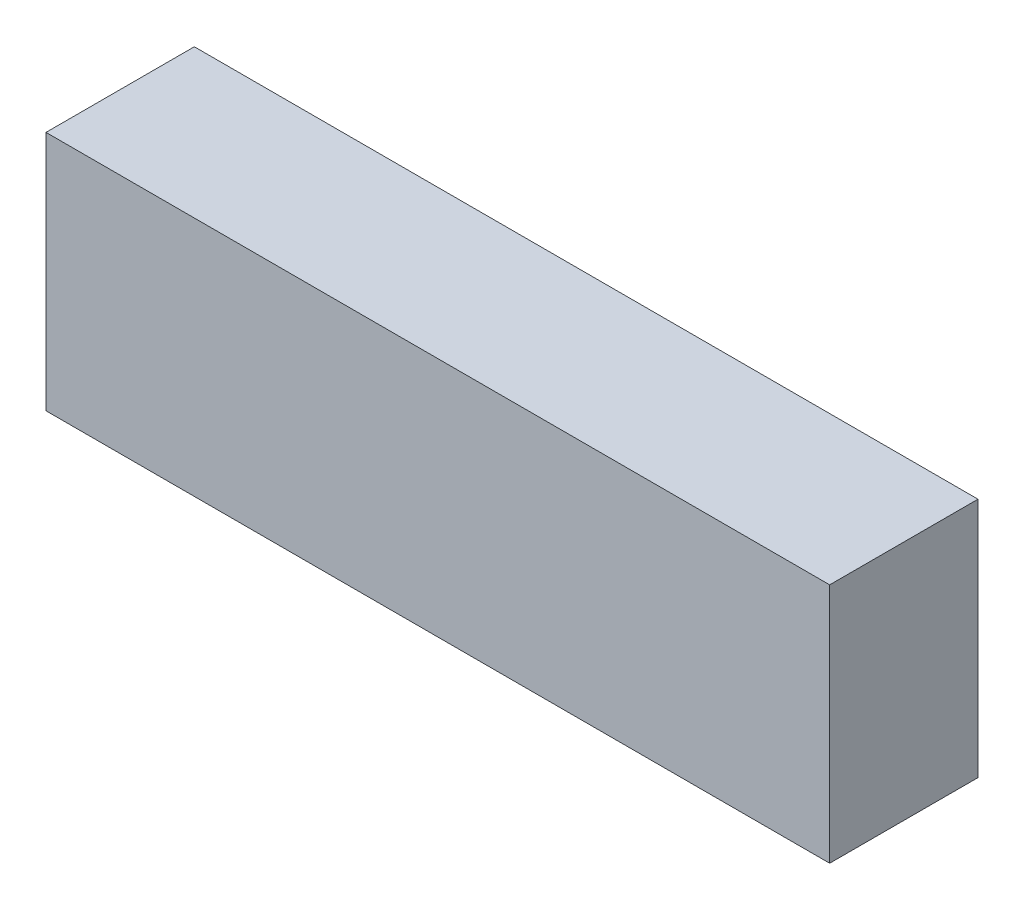
SolidWorks part; units mm, degrees
ref_plane "Front Plane" through (0, 0, 0) normal (0, 0, 1) x (1, 0, 0)
ref_plane "Top Plane" through (0, 0, 0) normal (0, 1, 0) x (1, 0, 0)
ref_plane "Right Plane" through (0, 0, 0) normal (1, 0, 0) x (0, 0, -1)
sketch "Sketch1" plane through (0, 0, 0) normal (0, 0, 1) x (1, 0, 0)
  line L0 (-2.6416, 0.8636) -> (2.6416, 0.8636)
  line L1 (2.6416, 0.8636) -> (2.6416, -0.762)
  line L2 (2.6416, -0.762) -> (-2.6416, -0.762)
  line L3 (-2.6416, -0.762) -> (-2.6416, 0.8636)
extrude "Component_Outline" add sketch "Sketch1" along normal blind 1 separate body
sketch3d "3DSketch1"
  line L0 (0, 0, 0) -> (1, 0, 0)
  line L1 (0, 0, 0) -> (0, 1, 0)
  line L2 (0, 0, 0) -> (0, 0, 1)
  point P0 (0, 0, 0)
